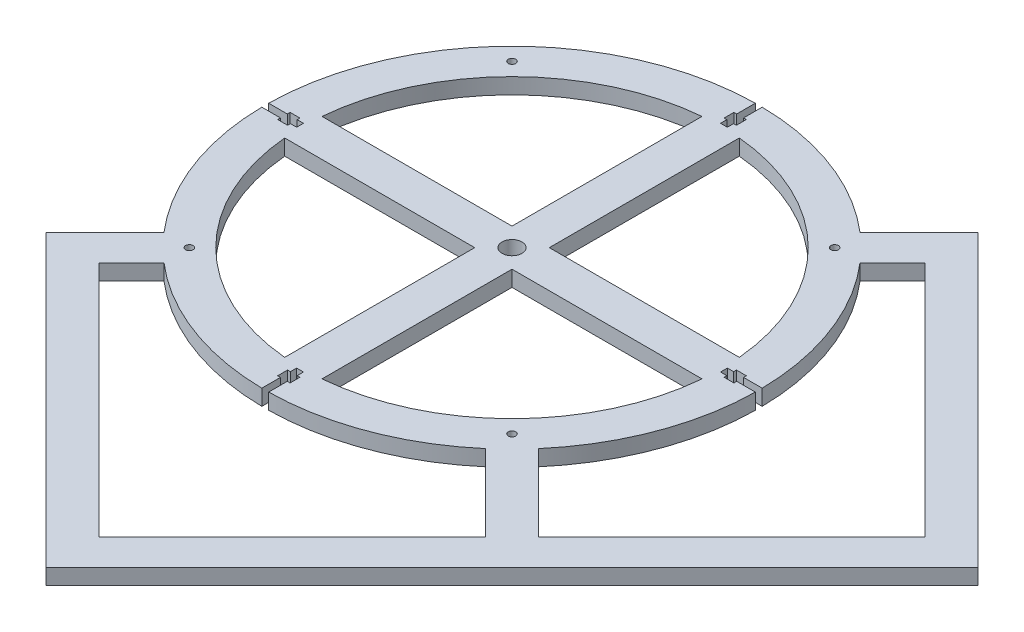
SolidWorks part; units mm, degrees
ref_plane "Front Plane" through (0, 0, 0) normal (0, 0, 1) x (1, 0, 0)
ref_plane "Top Plane" through (0, 0, 0) normal (0, 1, 0) x (1, 0, 0)
ref_plane "Right Plane" through (0, 0, 0) normal (1, 0, 0) x (0, 0, -1)
sketch "Sketch1" plane through (0, 0, 0) normal (0, 1, 0) x (1, 0, 0)
  line L0 (0, -99.238) -> (0, 99.238) construction
  line L1 (-99.238, 0) -> (99.238, 0) construction
  line L2 (-98.9542, -7.5) -> (98.9542, -7.5)
  line L3 (7.5, -98.9542) -> (7.5, 98.9542)
  line L4 (-98.9542, 7.5) -> (98.9542, 7.5)
  line L5 (-7.5, -98.9542) -> (-7.5, 98.9542)
  line L6 (-7.5, -99.238) -> (-7.5, 99.238) construction
  line L7 (7.5, -99.238) -> (7.5, 99.238) construction
  line L8 (-99.238, -7.5) -> (99.238, -7.5) construction
  line L9 (-99.238, 7.5) -> (99.238, 7.5) construction
  line L10 (-88.3883, -88.3883) -> (17.6777, -194.4544) construction
  line L11 (17.6777, -194.4544) -> (194.4544, -17.6777) construction
  line L12 (194.4544, -17.6777) -> (88.3883, 88.3883) construction
  line L13 (0, 0) -> (33755.9757, 33755.9757) construction
  line L14 (-88.3883, -88.3883) -> (-70.1719, -70.1719) construction
  line L15 (88.3883, 88.3883) -> (70.1719, 70.1719) construction
  line L16 (106.066, -106.066) -> (70.1719, -70.1719) construction
  line L17 (111.3693, -100.7627) -> (75.2745, -64.6679)
  line L18 (88.3883, 77.7817) -> (75.2745, 64.6679)
  line L19 (183.8478, -17.6777) -> (88.3883, 77.7817)
  line L20 (17.6777, -183.8478) -> (183.8478, -17.6777)
  line L21 (-77.7817, -88.3883) -> (17.6777, -183.8478)
  line L22 (-77.7817, -88.3883) -> (-64.6679, -75.2745)
  line L23 (100.7627, -111.3693) -> (64.6679, -75.2745)
  line L24 (88.3883, 98.9949) -> (64.6679, 75.2745)
  line L25 (205.061, -17.6777) -> (88.3883, 98.9949)
  line L26 (17.6777, -205.061) -> (205.061, -17.6777)
  line L27 (-98.9949, -88.3883) -> (17.6777, -205.061)
  line L28 (-98.9949, -88.3883) -> (-75.2745, -64.6679)
  line L29 (-77.7817, -88.3883) -> (-64.8686, -75.4752) construction
  line L30 (-98.9949, -88.3883) -> (-75.4752, -64.8686) construction
  line L31 (88.3883, 77.7817) -> (75.4752, 64.8686) construction
  line L32 (88.3883, 98.9949) -> (64.8686, 75.4752) construction
  line L33 (111.3693, -100.7627) -> (75.4752, -64.8686) construction
  line L34 (100.7627, -111.3693) -> (64.8686, -75.4752) construction
  circle A0 centre (0, 0) radius 100 construction
  circle A1 centre (0, 0) radius 99.238
  circle A2 centre (0, 0) radius 84.238
  point P7 (0, 0)
  point P11 (0, 0)
  dimension "D1" = 200
  dimension "D2" = 0.762
  dimension "D3" = 15
  dimension "D6" = 25
  dimension "D7" = 25
  dimension "D8" = 50
  dimension "D9" = 15
  dimension "D10" = 45
  dimension "D4" = 7.5
  dimension "D5" = 7.5
  dimension "D11" = 7.5
  dimension "D12" = 7.5
extrude "Boss-Extrude1" add sketch "Sketch1" along normal mid plane 6.35
sketch "Sketch2" plane through (0, 0, 0) normal (0, 1, 0) x (1, 0, 0)
  line L0 (-1.375, 85.238) -> (-1.375, 99.238)
  line L1 (-1.375, 85.238) -> (1.375, 85.238)
  line L2 (-1.375, 99.238) -> (1.375, 99.238)
  line L3 (1.375, 85.238) -> (1.375, 99.238)
  line L4 (-1.375, 85.238) -> (1.375, 99.238) construction
  line L5 (-1.375, 99.238) -> (1.375, 85.238) construction
  line L6 (-2.5, 87.738) -> (-2.5, 91.738)
  line L7 (-2.5, 87.738) -> (2.5, 87.738)
  line L8 (-2.5, 91.738) -> (2.5, 91.738)
  line L9 (2.5, 87.738) -> (2.5, 91.738)
  line L10 (-2.5, 87.738) -> (2.5, 91.738) construction
  line L11 (-2.5, 91.738) -> (2.5, 87.738) construction
  line L12 (0, -1000) -> (0, 49000) construction
  line L13 (-1000, 0) -> (49000, 0) construction
  circle A0 centre (0, 0) radius 99.238 construction
  point P1 (0, 92.238)
  point P2 (0, 89.738)
  dimension "D1" = 2.75
  dimension "D2" = 14
  dimension "D3" = 4
  dimension "D4" = 5
  dimension "D5" = 2.5
extrude "Cut-Extrude1" cut sketch "Sketch2" against normal through all both and the other way through all contours L7 L0 L1 L3 | L8 L0 L7 L3 | L7 L9 L8 L3 | L0 L8 L3 L2 | L8 L6 L7 L0
pattern_circular "CirPattern1" count 4 over 360 about axis through (0, 0, 0) along (0, 1, 0) of "Cut-Extrude1"
hole_wizard "Ø3.0 (3) Diameter Hole1" positions "Sketch3" profile "Sketch4" hole size "Ø3.0" standard "ANSI Metric" end condition up to next
sketch "Sketch3" plane through (0, 3.175, 0) normal (0, 1, 0) x (1, 0, 0)
  line L0 (-70.1719, -70.1719) -> (70.1719, 70.1719) construction
  line L2 (-70.1719, 70.1719) -> (70.1719, -70.1719) construction
  line L4 (70.1719, 70.1719) -> (59.5653, 59.5653)
  line L6 (70.1719, -70.1719) -> (59.5653, -59.5653)
  line L8 (-70.1719, -70.1719) -> (-59.5653, -59.5653)
  line L10 (-70.1719, 70.1719) -> (-59.5653, 59.5653)
  arc A2 (83.9035, 7.5) -> (7.5, 83.9035) centre (0, 0) ccw construction
  arc A3 (7.5, -83.9035) -> (83.9035, -7.5) centre (0, 0) ccw construction
  arc A4 (-83.9035, -7.5) -> (-7.5, -83.9035) centre (0, 0) ccw construction
  arc A5 (-7.5, 83.9035) -> (-83.9035, 7.5) centre (0, 0) ccw construction
  circle A6 centre (0, 0) radius 99.238
  arc A7 (-1.375, 99.2285) -> (-99.2285, 1.375) centre (0, 0) ccw construction
  point P107 (0, 0)
  point P324 (0, 0)
  point P360 (-64.8686, 64.8686)
  point P362 (64.8686, 64.8686)
  point P364 (64.8686, -64.8686)
  point P366 (-64.8686, -64.8686)
sketch "Sketch4" plane through (-64.8686, 3.175, 64.8686) normal (1, 0, 0) x (0, 0, 1)
  line L0 (0, 0) -> (0, 6.35)
  line L1 (0, 6.35) -> (1.5, 6.35)
  line L2 (1.5, 6.35) -> (1.5, 0)
  line L5 (1.5, 0) -> (0, 0)
  line L11 (0, -6.35) -> (0, 107.95) construction
  dimension "Thru Hole Dia." = 3
  dimension "Thru Hole Depth" = 6.35
hole_wizard "Ø8.0 (8) Diameter Hole1" positions "Sketch5" profile "Sketch6" hole size "Ø8.0" standard "ANSI Metric" end condition up to next
sketch "Sketch5" plane through (0, 3.175, 0) normal (0, 1, 0) x (1, 0, 0)
  point P0 (0, 0)
sketch "Sketch6" plane through (0, 3.175, 0) normal (1, 0, 0) x (0, 0, 1)
  line L0 (0, 0) -> (0, 6.35)
  line L1 (0, 6.35) -> (4, 6.35)
  line L2 (4, 6.35) -> (4, 0)
  line L5 (4, 0) -> (0, 0)
  line L11 (0, -6.35) -> (0, 107.95) construction
  dimension "Thru Hole Dia." = 8
  dimension "Thru Hole Depth" = 6.35
